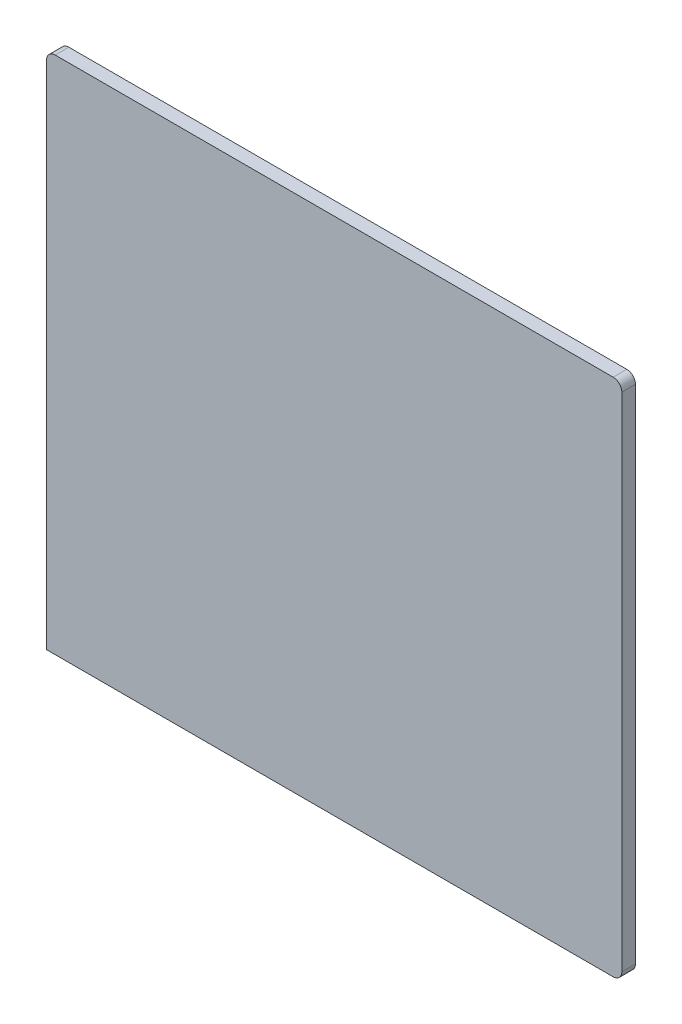
SolidWorks part; units mm, degrees
ref_plane "Front Plane" through (0, 0, 0) normal (0, 0, 1) x (1, 0, 0)
ref_plane "Top Plane" through (0, 0, 0) normal (0, 1, 0) x (1, 0, 0)
ref_plane "Right Plane" through (0, 0, 0) normal (1, 0, 0) x (0, 0, -1)
sketch "BPR2 PCB Outline" plane through (0, 0, 0) normal (0, 0, 1) x (1, 0, 0)
  line L0 (114.543, 7.1204) -> (102.643, 7.1204)
  line L1 (50.073, 67.1204) -> (114.543, 67.1204)
  line L2 (49.073, 66.1204) -> (49.073, 7.1204)
  line L3 (49.073, 7.1204) -> (82.643, 7.1204)
  line L4 (115.543, 66.1204) -> (115.543, 8.1204)
  line L9 (82.643, 7.1204) -> (102.643, 7.1204)
  arc A0 (114.543, 7.1204) -> (115.543, 8.1204) centre (114.543, 8.1204) ccw
  arc A1 (114.543, 67.1204) -> (115.543, 66.1204) centre (114.543, 66.1204) cw
  arc A2 (50.073, 67.1204) -> (49.073, 66.1204) centre (50.073, 66.1204) ccw
  point P6 (115.543, 7.1204)
  point P9 (115.543, 67.1204)
  point P12 (49.073, 67.1204)
  dimension "D2" = 66.47
  dimension "D4" = 11.9
  dimension "D3" = 1
  dimension "D1" = 60
sketch "23" plane through (0, 0, 0) normal (0, 0, 1) x (1, 0, 0)
  point P0 (0, 0)
extrude "Boss-Extrude1" add sketch "BPR2 PCB Outline" against normal blind 1.5748
